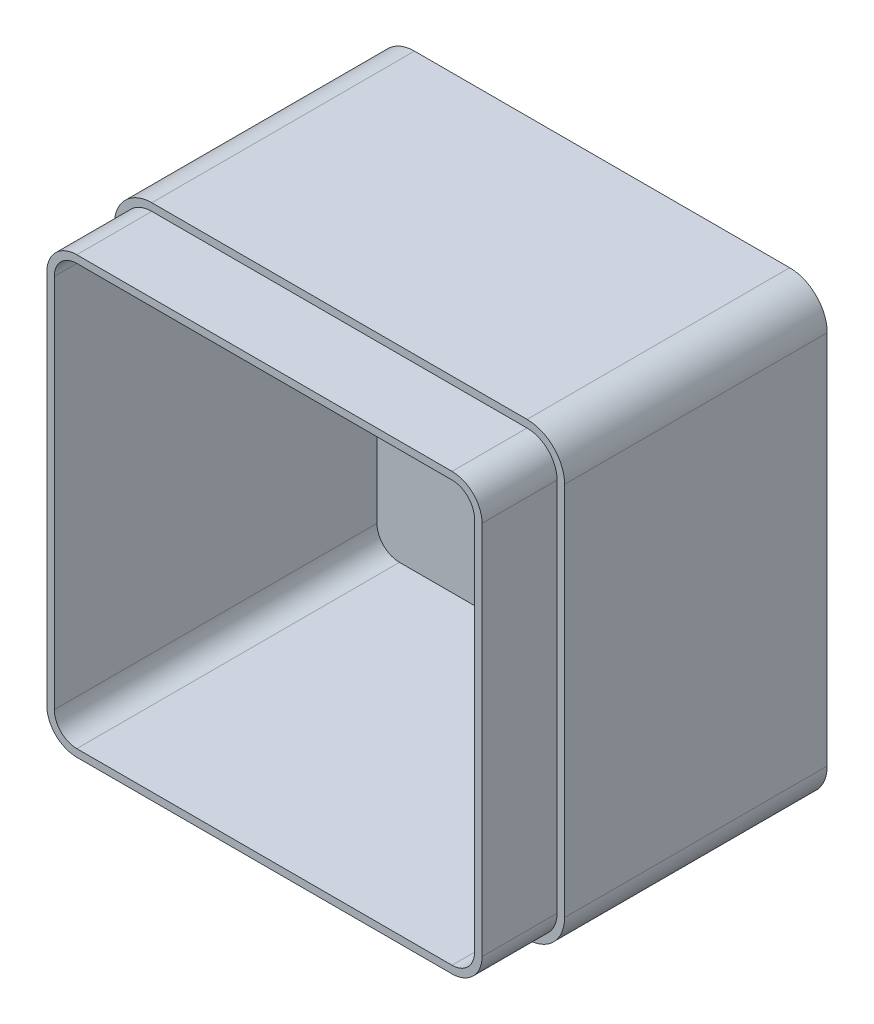
SolidWorks part; units mm, degrees
ref_plane "Front" through (0, 0, 0) normal (0, 0, 1) x (1, 0, 0)
ref_plane "Top" through (0, 0, 0) normal (0, 1, 0) x (1, 0, 0)
ref_plane "Right" through (0, 0, 0) normal (1, 0, 0) x (0, 0, -1)
sketch "草圖1" plane through (0, 0, 0) normal (0, 0, 1) x (1, 0, 0)
  line L1 (-60, 60) -> (60, 60)
  line L2 (-60, 60) -> (-60, -60)
  line L3 (-60, -60) -> (60, -60)
  line L4 (60, 60) -> (60, -60)
  line L5 (-60, 60) -> (60, -60) construction
  line L6 (-60, -60) -> (60, 60) construction
  point P0 (0, 0)
  dimension "D1" = 120
  dimension "D2" = 120
extrude "填料-伸長1" add sketch "草圖1" along normal blind 90
fillet "圓角1" radius 10 4 edges at (-60, -60, 45) (60, -60, 45) (60, 60, 45) (-60, 60, 45)
shell "薄殼1" thickness 4
sketch "草圖10" plane through (0, 0, 90) normal (0, 0, 1) x (1, 0, 0)
  line L0 (60, -50) -> (60, 50) construction
  line L1 (-50, -60) -> (50, -60) construction
  line L2 (-60, 50) -> (-60, -50) construction
  line L3 (50, 60) -> (-50, 60) construction
  line L4 (60, -50) -> (60, 50)
  line L5 (-50, -60) -> (50, -60)
  line L6 (-60, 50) -> (-60, -50)
  line L7 (50, 60) -> (-50, 60)
  line L16 (-58, 50) -> (-58, -50)
  line L17 (-50, -58) -> (50, -58)
  line L18 (58, -50) -> (58, 50)
  line L19 (50, 58) -> (-50, 58)
  line L20 (-58, 50) -> (-58, -50)
  line L21 (-50, -58) -> (50, -58)
  line L22 (58, -50) -> (58, 50)
  line L23 (50, 58) -> (-50, 58)
  arc A0 (60, 50) -> (50, 60) centre (50, 50) ccw construction
  arc A1 (50, -60) -> (60, -50) centre (50, -50) ccw construction
  arc A2 (-60, -50) -> (-50, -60) centre (-50, -50) ccw construction
  arc A3 (-50, 60) -> (-60, 50) centre (-50, 50) ccw construction
  arc A4 (60, 50) -> (50, 60) centre (50, 50) ccw
  arc A5 (50, -60) -> (60, -50) centre (50, -50) ccw
  arc A6 (-60, -50) -> (-50, -60) centre (-50, -50) ccw
  arc A7 (-50, 60) -> (-60, 50) centre (-50, 50) ccw
  arc A16 (-58, -50) -> (-50, -58) centre (-50, -50) ccw
  arc A17 (50, -58) -> (58, -50) centre (50, -50) ccw
  arc A18 (58, 50) -> (50, 58) centre (50, 50) ccw
  arc A19 (-50, 58) -> (-58, 50) centre (-50, 50) ccw
  arc A20 (-58, -50) -> (-50, -58) centre (-50, -50) ccw
  arc A21 (50, -58) -> (58, -50) centre (50, -50) ccw
  arc A22 (58, 50) -> (50, 58) centre (50, 50) ccw
  arc A23 (-50, 58) -> (-58, 50) centre (-50, 50) ccw
  dimension "D1" = 2
extrude "除料-伸長1" cut sketch "草圖10" against normal blind 20
